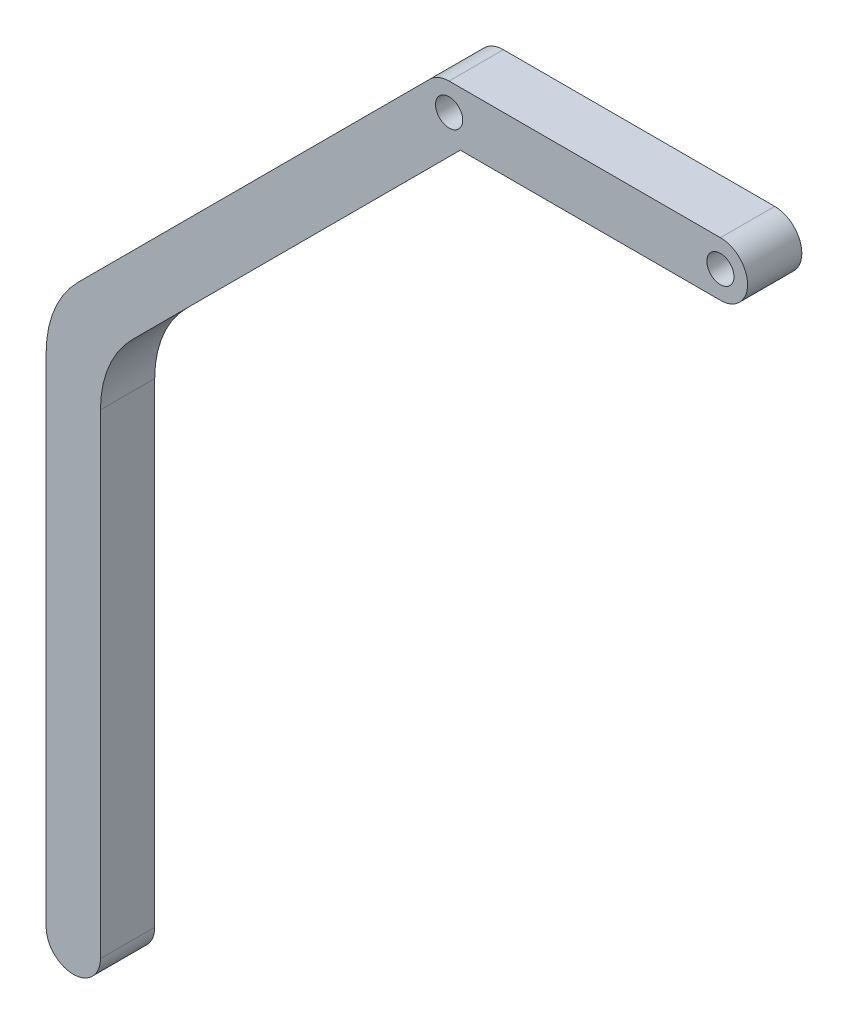
SolidWorks part; units mm, degrees
ref_plane "Front Plane" through (0, 0, 0) normal (0, 0, 1) x (1, 0, 0)
ref_plane "Top Plane" through (0, 0, 0) normal (0, 1, 0) x (1, 0, 0)
ref_plane "Right Plane" through (0, 0, 0) normal (1, 0, 0) x (0, 0, -1)
sketch "Sketch3" plane through (0, 0, 0) normal (0, 0, 1) x (1, 0, 0)
  line L0 (0, 5) -> (50, 5)
  line L1 (2.0711, -5) -> (50, -5)
  line L2 (-3.5355, 3.5355) -> (-68.3883, -61.3173)
  line L3 (0, 0) -> (-22.949, 0) construction
  line L4 (-74.2462, -75.4594) -> (-74.2462, -167.1751)
  line L5 (-64.2462, -167.1751) -> (-64.2462, -79.6016)
  line L6 (-58.3883, -65.4594) -> (2.0711, -5)
  circle A0 centre (0, 0) radius 2.5
  arc A1 (0, 5) -> (-3.5355, 3.5355) centre (0, 0) ccw
  circle A2 centre (50, 0) radius 2.5
  arc A3 (50, -5) -> (50, 5) centre (50, 0) ccw
  arc A4 (-74.2462, -167.1751) -> (-64.2462, -167.1751) centre (-69.2462, -167.1751) ccw
  arc A5 (-68.3883, -61.3173) -> (-74.2462, -75.4594) centre (-54.2462, -75.4594) ccw
  arc A6 (-64.2462, -79.6016) -> (-58.3883, -65.4594) centre (-44.2462, -79.6016) cw
  point P9 (0, 0)
  point P17 (0, 0)
  point P21 (-74.2462, -67.1751)
  dimension "D1" = 5
  dimension "D2" = 10
  dimension "D3" = 5
  dimension "D4" = 10
  dimension "D12" = 20
  dimension "D5" = 50
  dimension "D6" = 45
  dimension "D7" = 100
  dimension "D8" = 100
  dimension "D9" = 10
  dimension "D10" = 10
  dimension "D11" = 135
extrude "Boss-Extrude1" add sketch "Sketch3" along normal blind 10
